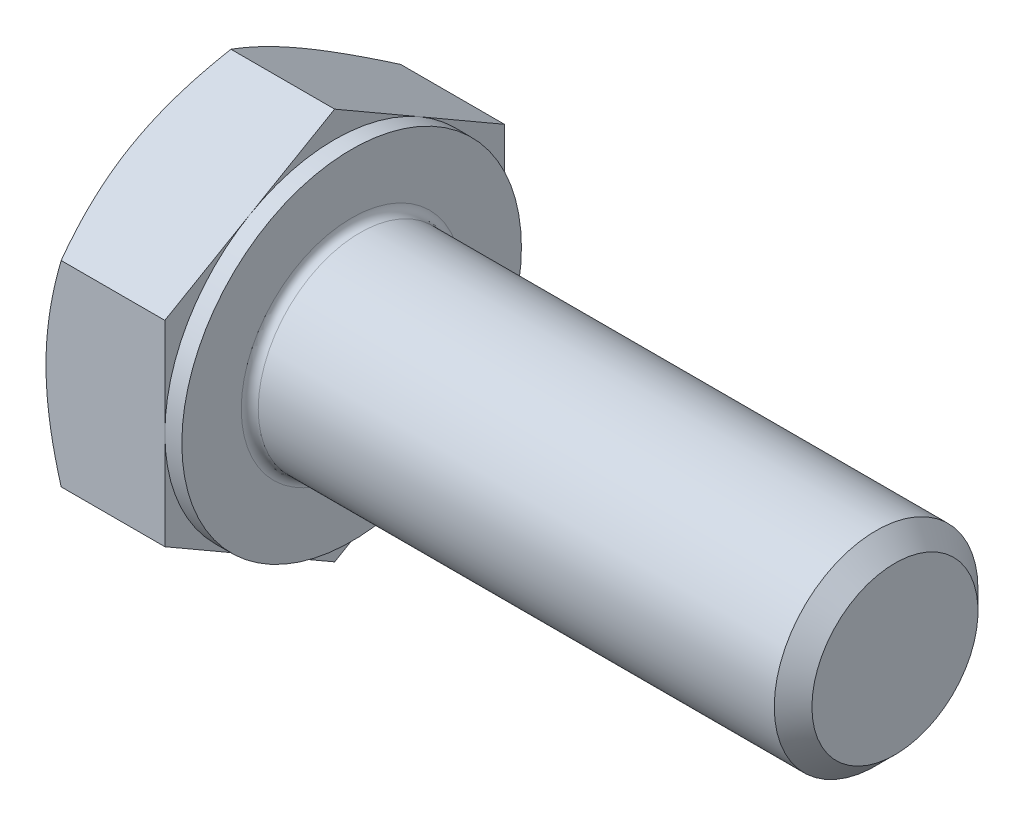
SolidWorks part; units mm, degrees
ref_plane "Plane1" through (0, 0, 0) normal (0, 0, 1) x (1, 0, 0)
ref_plane "Plane2" through (0, 0, 0) normal (0, 1, 0) x (1, 0, 0)
ref_plane "Plane3" through (0, 0, 0) normal (1, 0, 0) x (0, 0, -1)
sketch "Sketch1" plane through (0, 0, 0) normal (1, 0, 0) x (0, 0, -1)
  line L0 (5, 2.8868) -> (5, -2.8868)
  line L1 (-5, 2.8868) -> (-5, -2.8868)
  line L2 (5, -2.8868) -> (0, -5.7735)
  line L3 (0, -5.7735) -> (-5, -2.8868)
  line L4 (5, 2.8868) -> (0, 5.7735)
  line L5 (0, 5.7735) -> (-5, 2.8868)
  dimension "Width_flats" = 10
  dimension "D2" = 120
  dimension "D3" = 5
  dimension "D4" = 5
  dimension "D5" = 5
extrude "BaseHead" add sketch "Sketch1" along normal blind 4
sketch "BodySke" plane through (0, 0, 0) normal (0, 0, 1) x (1, 0, 0)
  line L0 (0, 2.8868) -> (0, -2.8868) construction
  line L1 (0, 0) -> (20, 0)
  line L2 (0, 0) -> (0, 3)
  line L3 (0, 3) -> (19.4455, 3)
  line L4 (20, 0) -> (20, 2.4455)
  line L5 (4, 5.7735) -> (4, 2.8868) construction
  line L6 (20, 2.4455) -> (19.4455, 3)
  line L7 (0, 0) -> (96.52, 0) construction
  line L8 (20, -2.4455) -> (19.4455, -3) construction
  line L9 (0, -3) -> (19.4455, -3) construction
  line L10 (5, 15.24) -> (5, -1.27) construction
  line L12 (4, 2.8868) -> (4, -2.8868) construction
  dimension "Length" = 16
  dimension "Body_ch_ang" = 45
  dimension "Diameter" = 6
  dimension "Minor_dia" = 4.891
  dimension "Advance" = 1
revolve "BaseBody" add sketch "BodySke" angle 360 about L7
cosmetic thread "Représentation de filetage4" parameters "D1"=14.5, "D2"=4.2
sketch "Sketch3" plane through (0, 0, 0) normal (0, 0, 1) x (1, 0, 0)
  line L0 (0, 5) -> (3.3333, 10.7735)
  line L1 (0, 5.7735) -> (0, 2.8868) construction
  line L2 (3.3333, 10.7735) -> (3.3333, 15.7735)
  line L3 (3.3333, 15.7735) -> (-10, 15.7735)
  line L4 (-10, 15.7735) -> (-10, 5)
  line L5 (-10, 5) -> (0, 5)
  line L6 (0, 0) -> (99.06, 0) construction
  line L7 (4, 5.7735) -> (0, 5.7735) construction
  dimension "D1" = 5
  dimension "D2" = 5
  dimension "D3" = 10
  dimension "D4" = 5
  dimension "Head_ch_ang" = 30
revolve "HeadChamfer" cut sketch "Sketch3" angle 360 about L6
sketch "Sketch4" plane through (0, 0, 0) normal (0, 0, 1) x (1, 0, 0)
  line L1 (4, 5.7735) -> (4, 2.8868) construction
  line L2 (4, 5) -> (3.5, 5)
  line L3 (4, 5) -> (4, 15.7735)
  line L4 (4, 15.7735) -> (3.5, 15.7735)
  line L5 (0, 0) -> (95.25, 0) construction
  line L6 (0, 0) -> (96.52, 0) construction
  line L7 (3.5, 5) -> (3.5, 15.7735)
  line L8 (4, 5.7735) -> (0.4466, 5.7735) construction
  dimension "D1" = 10
  dimension "D2" = 10
  dimension "Bearing_ht" = 0.5
revolve "BearingFace" cut sketch "Sketch4" angle 360 about L5
fillet "HeadFillet" radius 0.25 1 edges at (4, 0, -3)
